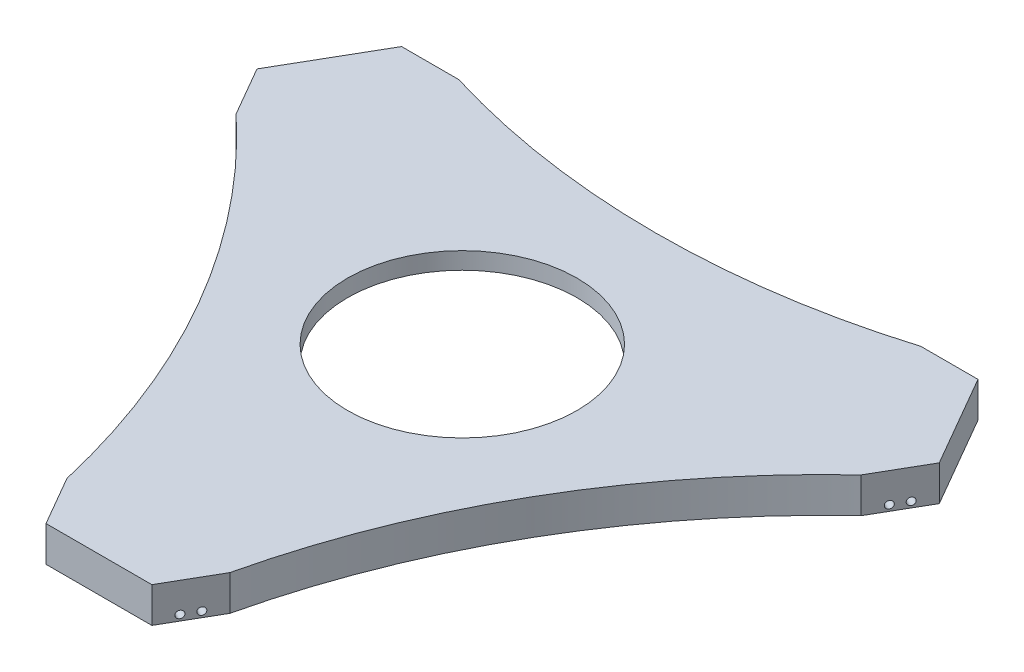
SolidWorks part; units mm, degrees
material "Prusament PETG"
ref_plane "Front Plane" through (0, 0, 0) normal (0, 0, 1) x (1, 0, 0)
ref_plane "Top Plane" through (0, 0, 0) normal (0, 1, 0) x (1, 0, 0)
ref_plane "Right Plane" through (0, 0, 0) normal (1, 0, 0) x (0, 0, -1)
sketch "Sketch1" plane through (0, 0, 0) normal (0, 1, 0) x (1, 0, 0)
  line L3 (-229.4685, 1.6326) -> (-226.0522, 7.5496) construction
  line L4 (-109.459, -194.3958) -> (3.718, 1.6326) construction
  line L5 (0.3018, 7.5496) -> (-226.0522, 7.5496) construction
  line L6 (-229.4685, 1.6326) -> (-116.2914, -194.3958) construction
  line L7 (0.3018, 7.5496) -> (3.718, 1.6326) construction
  line L8 (-109.459, -194.3958) -> (-116.2914, -194.3958) construction
  line L15 (-247.1214, 22.3992) -> (21.371, 22.3992) construction
  line L17 (-226.0522, 7.5496) -> (0.3018, 7.5496) construction
  line L18 (23.3241, -24.1079) -> (29.5486, -13.3268) construction
  line L19 (-267.4233, -20.3268) -> (-154.2863, -216.286) construction
  line L20 (-107.1335, -220.0671) -> (27.1128, 12.4542) construction
  line L21 (-252.8632, 12.4542) -> (-118.6169, -220.0671) construction
  line L22 (-267.4233, -20.3268) -> (-226.0123, 51.3992) construction
  line L24 (-68.8564, 7.5496) -> (-156.894, 7.5496) construction
  line L25 (-156.894, 7.5496) -> (-226.0522, 7.5496) construction
  line L26 (-68.8564, 7.5496) -> (0.3018, 7.5496) construction
  line L27 (-226.0123, 51.3992) -> (0.2619, 51.3992) construction
  line L28 (0.2619, 51.3992) -> (41.6729, -20.3268) construction
  line L29 (41.6729, -20.3268) -> (-71.4642, -216.286) construction
  line L30 (-71.4642, -216.286) -> (-154.2863, -216.286) construction
  line L31 (-226.0522, 7.5496) -> (-156.894, 7.5496) construction
  line L32 (-112.8752, -61.7379) -> (-112.8752, 367.8363) construction
  line L35 (-226.0123, 37.3992) -> (-213.5634, 37.3992)
  line L36 (-229.4685, 1.6326) -> (-116.2914, -194.3958) construction
  line L44 (-109.459, -194.3958) -> (3.718, 1.6326) construction
  line L47 (-83.5885, -209.286) -> (-77.3641, -198.505)
  line L48 (29.5486, -13.3268) -> (41.6729, -20.3268) construction
  line L49 (-83.5885, -209.286) -> (-71.4642, -216.286) construction
  line L50 (-142.1619, -209.286) -> (-154.2863, -216.286) construction
  line L51 (-255.299, -13.3268) -> (-267.4233, -20.3268) construction
  line L52 (-226.0123, 37.3992) -> (-226.0123, 51.3992) construction
  line L53 (0.2619, 37.3992) -> (0.2619, 51.3992) construction
  line L54 (29.5486, -13.3268) -> (35.773, -2.5458)
  line L55 (0.2619, 37.3992) -> (12.7108, 37.3992)
  line L56 (-83.5885, -209.286) -> (-89.813, -220.0671)
  line L57 (-142.1619, -209.286) -> (-135.9375, -220.0671)
  line L58 (-226.0123, 37.3992) -> (-238.4612, 37.3992)
  line L59 (-255.299, -13.3268) -> (-261.5234, -2.5458)
  line L60 (-261.5234, -2.5458) -> (-238.4612, 37.3992)
  line L61 (35.773, -2.5458) -> (12.7108, 37.3992)
  line L62 (-89.813, -220.0671) -> (-135.9375, -220.0671)
  line L63 (-255.299, -13.3268) -> (-249.0745, -24.1079)
  line L64 (259.1469, -276.525) -> (-112.8752, -61.7379) construction
  line L65 (-484.8973, -276.525) -> (-112.8752, -61.7379) construction
  line L66 (29.5486, -13.3268) -> (35.773, -2.5458) construction
  line L67 (-201.0888, 37.3992) -> (0.2619, 37.3992)
  line L68 (-148.3863, -198.505) -> (-142.1619, -209.286)
  line L69 (23.3241, -24.1079) -> (29.5486, -13.3268)
  circle A0 centre (-112.8752, -61.7379) radius 132.7019 construction
  circle A5 centre (-112.8752, -61.7379) radius 160 construction
  arc A9 (-213.5634, 37.3992) -> (-12.187, 37.3992) centre (-112.8752, 367.8363) ccw
  arc A10 (-148.3863, -198.505) -> (-249.0745, -24.1079) centre (-484.8973, -276.525) ccw
  arc A11 (23.3241, -24.1079) -> (-77.3641, -198.505) centre (259.1469, -276.525) ccw
  point P33 (-12.187, 37.3992)
  point P51 (-249.0745, -24.1079)
  point P52 (-213.5634, 37.3992)
  point P53 (-148.3863, -198.505)
  point P54 (-77.3641, -198.505)
  point P55 (23.3241, -24.1079)
  dimension "D1" = 320
  dimension "D3" = 265.4038
  dimension "Distance_of_servo_centre_of_rotation_to_edge" = 14
  dimension "D5" = 82.8221
  dimension "D6" = 15
  dimension "D7" = 15
  dimension "D8" = 15
  dimension "D2" = 30
  dimension "D4" = 90
extrude "Boss-Extrude2" add sketch "Sketch1" along normal blind 5.4 contours L59 L63 L57 L62 L56 L47 L54 L61 L55 L35 L58 L60
sketch "Sketch24" plane through (0, 5.4, 0) normal (0, 1, 0) x (1, 0, 0)
  circle A1 centre (-112.8752, -61.7379) radius 50
  dimension "D1" = 100
extrude "Cut-Extrude1" cut sketch "Sketch24" against normal through all
sketch "Sketch25" plane through (0, 0, -37.3992) normal (0, 0, -1) x (-1, 0, 0)
  circle A0 centre (226.0123, 2.7) radius 1.7887 construction
sketch "Sketch26" plane through (-197.2449, 0, 113.8794) normal (-0.866, 0, 0.5) x (0.5, 0, 0.866)
  line L0 (106.6661, 2.5) -> (113.6661, 2.5) construction
  line L1 (97.7172, 0) -> (122.615, 0) construction
  line L5 (106.6661, 2.5) -> (97.7172, 2.5) construction
  line L6 (97.7172, 5.4) -> (97.7172, 0) construction
  line L7 (113.6661, 2.5) -> (122.615, 2.5) construction
  line L8 (122.615, 5.4) -> (122.615, 0) construction
  circle A0 centre (106.6661, 2.5) radius 1.6
  circle A1 centre (113.6661, 2.5) radius 1.6
  dimension "D3" = 3.2
  dimension "D1" = 2.5
  dimension "D2" = 7
extrude "Cut-Extrude2" cut sketch "Sketch26" against normal blind 8.2
sketch "Sketch27" plane through (-197.2449, 0, 113.8794) normal (-0.866, 0, 0.5) x (0.5, 0, 0.866)
  line L0 (-119.6081, 2.5) -> (-112.6081, 2.5) construction
  line L1 (-119.6081, 2.5) -> (-128.557, 2.5) construction
  line L2 (-112.6081, 2.5) -> (-103.6592, 2.5) construction
  line L4 (-103.6592, 5.4) -> (-103.6592, 0) construction
  line L5 (-103.6592, 0) -> (-128.557, 0) construction
  circle A0 centre (-119.6081, 2.5) radius 1.6
  circle A1 centre (-112.6081, 2.5) radius 1.6
  dimension "D5" = 3.2
  dimension "D1" = 8.9489
  dimension "D2" = 8.9489
  dimension "D3" = 2.5
  dimension "D4" = 7
extrude "Cut-Extrude3" cut sketch "Sketch27" against normal blind 8.2
sketch "Sketch28" plane through (0, 0, -37.3992) normal (0, 0, -1) x (-1, 0, 0)
  line L0 (222.5123, 2.5) -> (229.5123, 2.5) construction
  line L1 (222.5123, 2.5) -> (213.5634, 2.5) construction
  line L2 (229.5123, 2.5) -> (238.4612, 2.5) construction
  line L3 (238.4612, 5.4) -> (238.4612, 0) construction
  line L4 (238.4612, 0) -> (213.5634, 0) construction
  circle A0 centre (222.5123, 2.5) radius 1.6
  circle A1 centre (229.5123, 2.5) radius 1.6
  dimension "D5" = 3.2
  dimension "D1" = 8.9489
  dimension "D2" = 8.9489
  dimension "D3" = 7
  dimension "D4" = 2.5
extrude "Cut-Extrude4" cut sketch "Sketch28" against normal blind 8.2
sketch "Sketch29" plane through (0, 0, -37.3992) normal (0, 0, -1) x (-1, 0, 0)
  line L0 (-3.7619, 2.5) -> (3.2381, 2.5) construction
  line L1 (-3.7619, 2.5) -> (-12.7108, 2.5) construction
  line L2 (3.2381, 2.5) -> (12.187, 2.5) construction
  line L3 (12.187, 0) -> (-12.7108, 0) construction
  line L4 (12.187, 5.4) -> (12.187, 0) construction
  circle A0 centre (-3.7619, 2.5) radius 1.6
  circle A1 centre (3.2381, 2.5) radius 1.6
  dimension "D5" = 3.2
  dimension "D1" = 8.9489
  dimension "D2" = 8.9489
  dimension "D3" = 7
  dimension "D4" = 2.5
extrude "Cut-Extrude5" cut sketch "Sketch29" against normal blind 8.2
sketch "Sketch30" plane through (27.9321, 0, 16.1266) normal (0.866, 0, 0.5) x (0.5, 0, -0.866)
  line L0 (-0.2671, 2.5) -> (6.7329, 2.5) construction
  line L1 (-0.2671, 2.5) -> (-9.216, 2.5) construction
  line L2 (6.7329, 2.5) -> (15.6818, 2.5) construction
  line L3 (-9.216, 0) -> (15.6818, 0) construction
  line L4 (15.6818, 5.4) -> (15.6818, 0) construction
  circle A0 centre (-0.2671, 2.5) radius 1.6
  circle A1 centre (6.7329, 2.5) radius 1.6
  dimension "D5" = 3.2
  dimension "D1" = 8.9489
  dimension "D2" = 8.9489
  dimension "D3" = 7
  dimension "D4" = 2.5
extrude "Cut-Extrude6" cut sketch "Sketch30" against normal blind 8.2
sketch "Sketch31" plane through (27.9321, 0, 16.1266) normal (0.866, 0, 0.5) x (0.5, 0, -0.866)
  line L0 (-226.5413, 2.5) -> (-219.5413, 2.5) construction
  line L1 (-226.5413, 2.5) -> (-235.4902, 2.5) construction
  line L2 (-219.5413, 2.5) -> (-210.5924, 2.5) construction
  line L3 (-210.5924, 0) -> (-235.4902, 0) construction
  line L4 (-210.5924, 5.4) -> (-210.5924, 0) construction
  circle A0 centre (-226.5413, 2.5) radius 1.6
  circle A1 centre (-219.5413, 2.5) radius 1.6
  dimension "D5" = 3.2
  dimension "D1" = 8.9489
  dimension "D2" = 8.9489
  dimension "D3" = 7
  dimension "D4" = 2.5
extrude "Cut-Extrude7" cut sketch "Sketch31" against normal blind 8.2
sketch "Sketch32" plane through (0, 5.4, 0) normal (0, 1, 0) x (1, 0, 0)
  line L0 (-229.4685, 1.6326) -> (-226.0522, 7.5496) construction
  line L1 (-109.459, -194.3958) -> (3.718, 1.6326) construction
  line L2 (0.3018, 7.5496) -> (-226.0522, 7.5496) construction
  line L3 (-229.4685, 1.6326) -> (-116.2914, -194.3958) construction
  line L4 (0.3018, 7.5496) -> (3.718, 1.6326) construction
  line L5 (-109.459, -194.3958) -> (-116.2914, -194.3958) construction
  line L6 (-247.1214, 22.3992) -> (21.371, 22.3992) construction
  line L7 (-226.0522, 7.5496) -> (0.3018, 7.5496) construction
  line L8 (23.3241, -24.1079) -> (29.5486, -13.3268) construction
  line L9 (-267.4233, -20.3268) -> (-154.2863, -216.286) construction
  line L10 (-107.1335, -220.0671) -> (27.1128, 12.4542) construction
  line L11 (-252.8632, 12.4542) -> (-118.6169, -220.0671) construction
  line L12 (-267.4233, -20.3268) -> (-226.0123, 51.3992) construction
  line L13 (-68.8564, 7.5496) -> (-156.894, 7.5496) construction
  line L14 (-156.894, 7.5496) -> (-226.0522, 7.5496) construction
  line L15 (-68.8564, 7.5496) -> (0.3018, 7.5496) construction
  line L16 (-226.0123, 51.3992) -> (0.2619, 51.3992) construction
  line L17 (0.2619, 51.3992) -> (41.6729, -20.3268) construction
  line L18 (41.6729, -20.3268) -> (-71.4642, -216.286) construction
  line L19 (-71.4642, -216.286) -> (-154.2863, -216.286) construction
  line L20 (-226.0522, 7.5496) -> (-156.894, 7.5496) construction
  line L21 (-226.0123, 37.3992) -> (-213.5634, 37.3992)
  line L22 (-229.4685, 1.6326) -> (-116.2914, -194.3958) construction
  line L23 (-109.459, -194.3958) -> (3.718, 1.6326) construction
  line L24 (-83.5885, -209.286) -> (-77.3641, -198.505)
  line L25 (29.5486, -13.3268) -> (41.6729, -20.3268) construction
  line L26 (-83.5885, -209.286) -> (-71.4642, -216.286) construction
  line L27 (-142.1619, -209.286) -> (-154.2863, -216.286) construction
  line L28 (-255.299, -13.3268) -> (-267.4233, -20.3268) construction
  line L29 (-226.0123, 37.3992) -> (-226.0123, 51.3992) construction
  line L30 (0.2619, 37.3992) -> (0.2619, 51.3992) construction
  line L31 (29.5486, -13.3268) -> (35.773, -2.5458)
  line L32 (0.2619, 37.3992) -> (12.7108, 37.3992)
  line L33 (-83.5885, -209.286) -> (-89.813, -220.0671)
  line L34 (-142.1619, -209.286) -> (-135.9375, -220.0671)
  line L35 (-226.0123, 37.3992) -> (-238.4612, 37.3992)
  line L36 (-255.299, -13.3268) -> (-261.5234, -2.5458)
  line L37 (-261.5234, -2.5458) -> (-238.4612, 37.3992)
  line L38 (35.773, -2.5458) -> (12.7108, 37.3992)
  line L39 (-89.813, -220.0671) -> (-135.9375, -220.0671)
  line L40 (-255.299, -13.3268) -> (-249.0745, -24.1079)
  line L41 (29.5486, -13.3268) -> (35.773, -2.5458) construction
  line L42 (-12.187, 37.3992) -> (0.2619, 37.3992)
  line L43 (-148.3863, -198.505) -> (-142.1619, -209.286)
  line L44 (23.3241, -24.1079) -> (29.5486, -13.3268)
  circle A0 centre (-112.8752, -61.7379) radius 132.7019 construction
  circle A1 centre (-112.8752, -61.7379) radius 160 construction
  arc A2 (-213.5634, 37.3992) -> (-12.187, 37.3992) centre (-112.8752, 367.8363) ccw
  arc A3 (-148.3863, -198.505) -> (-249.0745, -24.1079) centre (-484.8973, -276.525) ccw
  arc A4 (23.3241, -24.1079) -> (-77.3641, -198.505) centre (259.1469, -276.525) ccw
  circle A5 centre (-112.8752, -61.7379) radius 50 construction
  circle A6 centre (-112.8752, -61.7379) radius 50
  point P29 (-10.8041, 38.4141)
  point P45 (-247.6916, -23.093)
  point P46 (-212.1804, 38.4141)
  point P47 (-147.0034, -197.4901)
  point P48 (-75.9811, -197.4901)
  point P49 (23.3241, -24.1079)
  dimension "D1" = 265.4038
  dimension "D2" = 14
  dimension "D3" = 82.8221
  dimension "D4" = 15
  dimension "D5" = 15
  dimension "D6" = 15
extrude "Boss-Extrude3" add sketch "Sketch32" along normal blind 10
sketch "Sketch33" plane through (0, 15.4, 0) normal (0, 1, 0) x (1, 0, 0)
  line L0 (-112.8752, -220.0671) -> (-112.8752, 22.3992) construction
  line L2 (-130.0375, -202.286) -> (-127.8546, -206.0671)
  line L3 (-135.2298, -193.2929) -> (-130.0375, -202.286)
  line L4 (-243.1746, -6.3268) -> (-237.9824, -15.32)
  line L5 (-243.1746, -6.3268) -> (-245.3576, -2.5458)
  line L6 (-245.3576, -2.5458) -> (-230.3783, 23.3992)
  line L7 (-226.0123, 23.3992) -> (-230.3783, 23.3992)
  line L9 (-226.0123, 23.3992) -> (-215.6279, 23.3992)
  line L10 (-97.8959, -206.0671) -> (-127.8546, -206.0671)
  line L11 (-95.7129, -202.286) -> (-97.8959, -206.0671)
  line L15 (0.2619, 23.3992) -> (-10.1225, 23.3992)
  line L16 (0.2619, 23.3992) -> (4.6279, 23.3992)
  line L17 (19.6072, -2.5458) -> (4.6279, 23.3992)
  line L18 (17.4242, -6.3268) -> (19.6072, -2.5458)
  line L19 (17.4242, -6.3268) -> (12.232, -15.32)
  line L22 (-90.5207, -193.2929) -> (-95.7129, -202.286)
  arc A5 (-135.2298, -193.2929) -> (-237.9824, -15.32) centre (-484.8973, -276.525) ccw
  arc A6 (-215.6279, 23.3992) -> (-112.8752, 8.3992) centre (-112.8752, 367.8363) ccw
  arc A7 (-10.1225, 23.3992) -> (-112.8752, 8.3992) centre (-112.8752, 367.8363) cw
  arc A8 (-90.5207, -193.2929) -> (12.232, -15.32) centre (259.1469, -276.525) cw
  circle A9 centre (-112.8752, -61.7379) radius 145.1044 construction
  point P3 (-123.8131, -213.0671)
  point P14 (-112.8752, -206.0671)
  point P15 (-135.9375, -206.0671)
  point P45 (-241.0247, -67.6455)
  point P47 (-140.3365, -242.0426)
  point P48 (-69.3142, -242.0426)
sketch "Sketch36" plane through (0, 0, 0) normal (0, -1, 0) x (1, 0, 0)
  line L0 (24.2419, -17.4267) -> (-185.7401, 103.8064) construction
  line L16 (-126.8249, 209.8506) -> (-137.3303, 191.6546)
  line L17 (-148.3863, 198.505) -> (-135.9375, 220.0671) construction
  line L18 (-112.8752, 220.0671) -> (-112.8752, -22.3992) construction
  line L19 (-89.813, 220.0671) -> (-135.9375, 220.0671) construction
  line L20 (-126.8249, 209.8506) -> (-98.9256, 209.8506)
  line L21 (-261.5234, 2.5458) -> (-238.4612, -37.3992) construction
  line L22 (-249.9923, -17.4267) -> (-40.0104, 103.8064) construction
  line L23 (-137.3303, 191.6546) -> (-164.3237, 91.4417)
  line L24 (-98.9256, 209.8506) -> (-88.4201, 191.6546)
  line L25 (-88.4201, 191.6546) -> (-61.4267, 91.4417)
  line L26 (-248.1194, -0.2377) -> (-234.1697, -24.3992)
  line L27 (-248.1194, -0.2377) -> (-237.6139, 17.9583)
  line L28 (-237.6139, 17.9583) -> (-164.3237, 91.4417)
  line L29 (11.8635, 17.9583) -> (-61.4267, 91.4417)
  line L30 (22.3689, -0.2377) -> (11.8635, 17.9583)
  line L31 (8.4193, -24.3992) -> (22.3689, -0.2377)
  line L32 (8.4193, -24.3992) -> (-12.5916, -24.3992)
  line L33 (-12.5916, -24.3992) -> (-112.8752, 2.3303)
  line L34 (-213.1588, -24.3992) -> (-112.8752, 2.3303)
  line L35 (-234.1697, -24.3992) -> (-213.1588, -24.3992)
  circle A4 centre (-112.8752, 61.7379) radius 145.1044 construction
  arc A5 (-12.187, -37.3992) -> (-213.5634, -37.3992) centre (-112.8752, -367.8363) ccw construction
  arc A6 (-77.3641, 198.505) -> (23.3241, 24.1079) centre (259.1469, 276.525) ccw construction
  point P25 (-112.8752, 209.8506)
  dimension "D1" = 13
extrude "Cut-Extrude10" cut sketch "Sketch36" against normal blind 8
equation "\"Hexagon_long_side_length\"= 2 * \"Matlab_Diameter_enclosing_circle\" / 2 * sin ( \"theta_long_side\" / 2 )"
equation "\"Hexagon_short_side_length\"= 2 * \"Matlab_Diameter_enclosing_circle\" / 2 * sin ( \"theta_short_side\" / 2 )"
equation "\"Width_upper_lower_shell\"= 0.0054"
equation "\"D1@Boss-Extrude2\"=\"Width_upper_lower_shell\""
equation "\"inner_Hole_diameter\"= 0.1m"
equation "\"holes_distance_from edge\"= \"Hexagon_short_side_length\" / 4m"
equation "\"holes_distance_from_eachother\"= 0.01"
equation "\"holes_distance_from_top\"= \"Width_upper_lower_shell\" / 2"
equation "\"theta_short_side\"= 30deg"
equation "\"theta_long_side\"= 120deg - \"theta_short_side\""
equation "\"Diametre_enclosing_circle\"= \"Matlab_Diameter_enclosing_circle\" * 0.75"
equation "\"Radius_enclosing_circle\"= \"Diametre_enclosing_circle\" / 2"
equation "\"Matlab_Diameter_enclosing_circle\"= 320mm"
equation "\"Distance_of_servo_centre_of_rotation_to_edge\"= 1.4cm"
equation "\"D1@Sketch1\"=\"Matlab_Diameter_enclosing_circle\""
equation "\"D2@Sketch1\" = \"theta_short_side\""
equation "\"distance of line tangent to circle\"= 1.5cm"
equation "\"D6@Sketch1\"=\"distance of line tangent to circle\""
equation "\"D7@Sketch1\"=\"distance of line tangent to circle\""
equation "\"D8@Sketch1\"=\"distance of line tangent to circle\""
equation "\"D1@Sketch24\"=\"inner_Hole_diameter\""
equation "\"servo_holes_diameter_3D_Print\"= 3.2mm"
equation "\"D5@Sketch28\"=\"servo_holes_diameter_3D_Print\""
equation "\"D5@Sketch27\"=\"servo_holes_diameter_3D_Print\""
equation "\"D3@Sketch26\"=\"servo_holes_diameter_3D_Print\""
equation "\"D5@Sketch29\"=\"servo_holes_diameter_3D_Print\""
equation "\"D5@Sketch30\"=\"servo_holes_diameter_3D_Print\""
equation "\"D5@Sketch31\"=\"servo_holes_diameter_3D_Print\""
